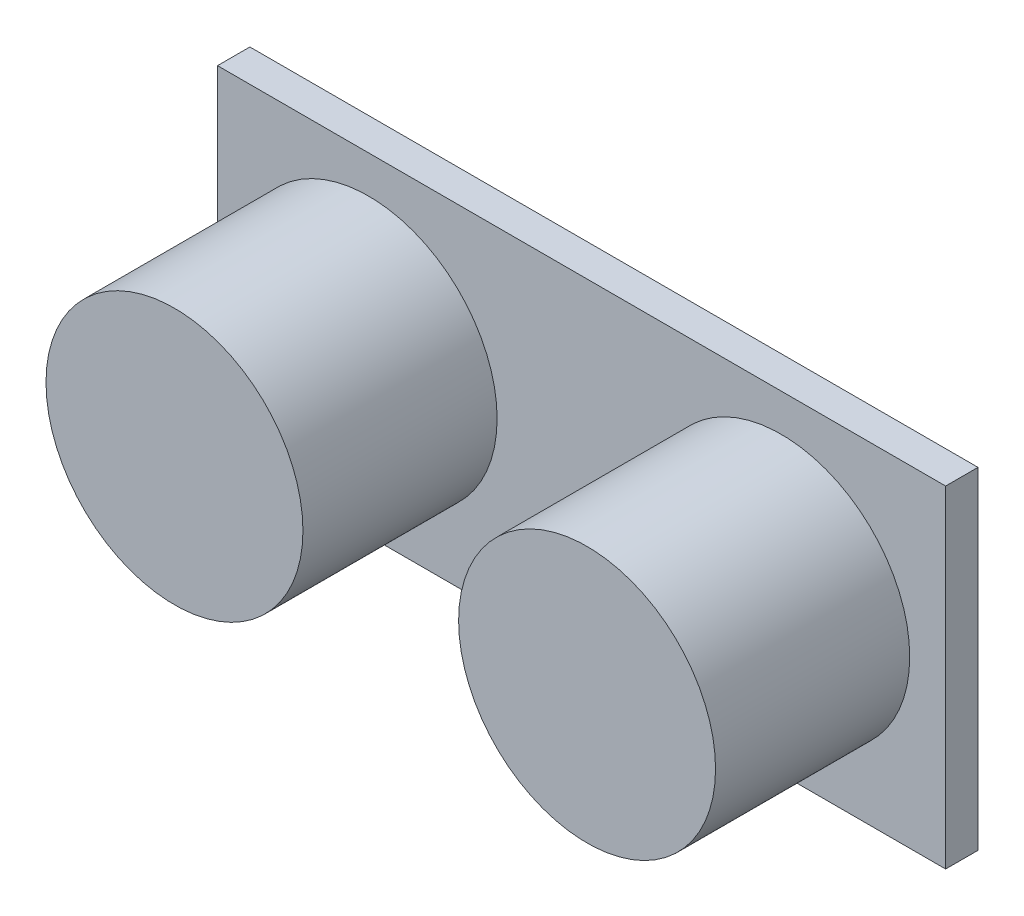
SolidWorks part; units mm, degrees
ref_plane "정면" through (0, 0, 0) normal (0, 0, 1) x (1, 0, 0)
ref_plane "윗면" through (0, 0, 0) normal (0, 1, 0) x (1, 0, 0)
ref_plane "우측면" through (0, 0, 0) normal (1, 0, 0) x (0, 0, -1)
sketch "스케치1" plane through (0, 0, 0) normal (0, 0, 1) x (1, 0, 0)
  line L1 (-22.5, 10.25) -> (22.5, 10.25)
  line L2 (-22.5, 10.25) -> (-22.5, -10.25)
  line L3 (-22.5, -10.25) -> (22.5, -10.25)
  line L4 (22.5, 10.25) -> (22.5, -10.25)
  line L5 (-22.5, 10.25) -> (22.5, -10.25) construction
  line L6 (-22.5, -10.25) -> (22.5, 10.25) construction
  point P0 (0, 0)
  dimension "D1" = 45
  dimension "D2" = 20.5
extrude "보스-돌출1" add sketch "스케치1" along normal blind 2
sketch "스케치2" plane through (0, 0, 2) normal (0, 0, 1) x (1, 0, 0)
  circle A0 centre (-13.16, 0) radius 7.94
  dimension "D3" = 15.88
sketch "스케치3" plane through (0, 0, 2) normal (0, 0, 1) x (1, 0, 0)
  line L1 (22.5, 10.25) -> (12.34, 10.25)
  line L2 (22.5, 10.25) -> (22.5, 0)
  line L3 (22.5, 0) -> (12.34, 0)
  line L4 (12.34, 10.25) -> (12.34, 0)
  circle A0 centre (12.34, 0) radius 7.94
  dimension "D3" = 15.88
  dimension "D1" = 10.16
  dimension "D2" = 10.25
extrude "보스-돌출2" add sketch "스케치2" along normal blind 12 contours A0
extrude "보스-돌출3" add sketch "스케치3" along normal blind 12 contours A0
